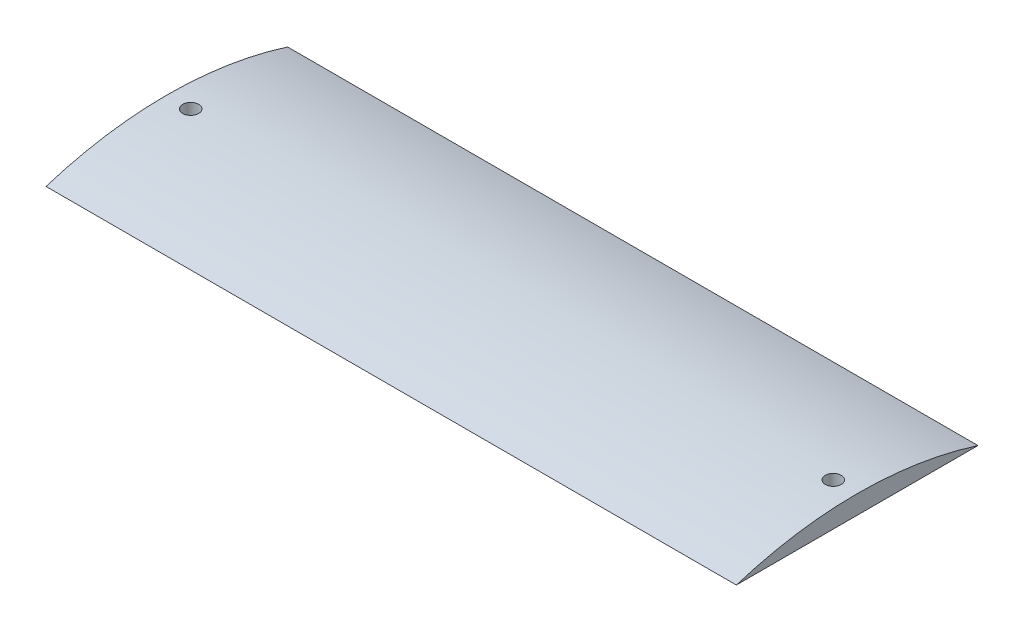
SolidWorks part; units mm, degrees
ref_plane "Front Plane" through (0, 0, 0) normal (0, 0, 1) x (1, 0, 0)
ref_plane "Top Plane" through (0, 0, 0) normal (0, 1, 0) x (1, 0, 0)
ref_plane "Right Plane" through (0, 0, 0) normal (1, 0, 0) x (0, 0, -1)
sketch "Sketch1" plane through (0, 0, 0) normal (1, 0, 0) x (0, 0, -1)
  line L3 (-22.75, -1) -> (22.75, -1)
  line L5 (0, 0) -> (22.75, -1) construction
  line L6 (-22.75, -1) -> (0, 0) construction
  arc A0 (-22.75, -1) -> (22.75, -1) centre (0, -72.4892) cw
  point P0 (0, 0)
  dimension "D1" = 45.5
extrude "Boss-Extrude1" add sketch "Sketch1" along normal blind 130
sketch "Sketch2" plane through (0, -1, 0) normal (0, -1, 0) x (-1, 0, 0)
  line L0 (-130, 0) -> (0, 0) construction
  line L1 (-130, -22.75) -> (-130, 22.75) construction
  line L2 (-65, 22.75) -> (-65, -22.75) construction
  line L3 (-130, 22.75) -> (0, 22.75) construction
  line L4 (-130, -22.75) -> (0, -22.75) construction
  line L7 (0, -22.75) -> (0, 22.75) construction
  circle A0 centre (-4.5, 0) radius 1.5
  circle A1 centre (-125.5, 0) radius 1.5
  dimension "D1" = 0
  dimension "D2" = 3
  dimension "D3" = 4.5
extrude "Cut-Extrude1" cut sketch "Sketch2" against normal up to next
